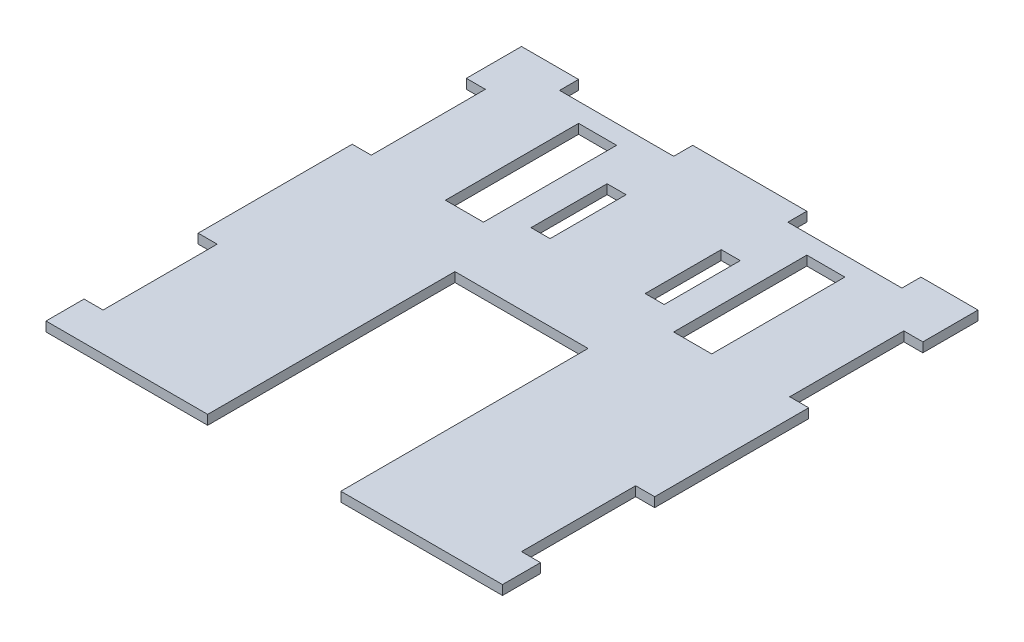
SolidWorks part; units mm, degrees
ref_plane "Front Plane" through (0, 0, 0) normal (0, 0, 1) x (1, 0, 0)
ref_plane "Top Plane" through (0, 0, 0) normal (0, 1, 0) x (1, 0, 0)
ref_plane "Right Plane" through (0, 0, 0) normal (1, 0, 0) x (0, 0, -1)
sketch "Sketch1" plane through (0, 0, 0) normal (0, 1, 0) x (1, 0, 0)
  line L0 (0, -3.4925) -> (0, 3.4925) construction
  line L1 (-152.4, -76.2) -> (152.4, -76.2)
  line L2 (-152.4, -76.2) -> (-152.4, 76.2)
  line L3 (-152.4, 76.2) -> (152.4, 76.2)
  line L4 (152.4, -76.2) -> (152.4, 76.2)
  line L5 (-152.4, -76.2) -> (152.4, 76.2) construction
  line L6 (-152.4, 76.2) -> (152.4, -76.2) construction
  line L7 (-152.4, -76.2) -> (-31.75, -76.2)
  line L8 (-152.4, -76.2) -> (-152.4, -241.3)
  line L9 (-152.4, -241.3) -> (-31.75, -241.3)
  line L10 (-31.75, -76.2) -> (-31.75, -241.3)
  line L11 (31.75, -76.2) -> (31.75, -241.3)
  line L12 (152.4, -241.3) -> (31.75, -241.3)
  line L13 (152.4, -76.2) -> (152.4, -241.3)
  line L14 (152.4, -76.2) -> (31.75, -76.2)
  line L15 (-44.45, -76.2) -> (-44.45, -241.3)
  line L16 (44.45, -76.2) -> (44.45, -241.3)
  point P0 (0, 0)
  dimension "D1" = 304.8
  dimension "D2" = 152.4
  dimension "D3" = 317.5
  dimension "D4" = 120.65
  dimension "D5" = 12.7
extrude "Boss-Extrude1" add sketch "Sketch1" along normal blind 6.35 contours L15 L1 L8 L9 | L14 L16 L12 L13 | L1 L7 L14 L4 L3 L2
sketch "Sketch2" plane through (0, 6.35, 0) normal (0, 1, 0) x (1, 0, 0)
  line L0 (152.4, -241.3) -> (152.4, 76.2) construction
  line L1 (152.4, 39.37) -> (139.7, 39.37)
  line L2 (152.4, 39.37) -> (152.4, -36.83)
  line L3 (152.4, -36.83) -> (139.7, -36.83)
  line L4 (139.7, 39.37) -> (139.7, -36.83)
  line L5 (-152.4, 76.2) -> (152.4, 76.2) construction
  line L6 (152.4, -139.7) -> (139.7, -139.7)
  line L7 (152.4, -139.7) -> (152.4, -215.9)
  line L8 (152.4, -215.9) -> (139.7, -215.9)
  line L9 (139.7, -139.7) -> (139.7, -215.9)
  line L10 (0, -3.4925) -> (0, 3.4925) construction
  line L11 (-152.4, -215.9) -> (-139.7, -215.9)
  line L12 (-139.7, -139.7) -> (-139.7, -215.9)
  line L13 (-152.4, -139.7) -> (-139.7, -139.7)
  line L14 (-152.4, -139.7) -> (-152.4, -215.9)
  line L15 (-152.4, -36.83) -> (-139.7, -36.83)
  line L16 (-139.7, 39.37) -> (-139.7, -36.83)
  line L17 (-152.4, 39.37) -> (-139.7, 39.37)
  line L18 (-152.4, 39.37) -> (-152.4, -36.83)
  line L19 (-114.3, 63.5) -> (-38.1, 63.5)
  line L20 (114.3, 76.2) -> (38.1, 76.2)
  line L21 (114.3, 76.2) -> (114.3, 63.5)
  line L22 (114.3, 63.5) -> (38.1, 63.5)
  line L23 (38.1, 76.2) -> (38.1, 63.5)
  line L24 (-38.1, 76.2) -> (-38.1, 63.5)
  line L25 (-114.3, 76.2) -> (-38.1, 76.2)
  line L26 (-114.3, 76.2) -> (-114.3, 63.5)
  line L27 (-88.9, -38.1) -> (-63.5, -38.1)
  line L28 (88.9, 50.8) -> (63.5, 50.8)
  line L29 (88.9, 50.8) -> (88.9, -38.1)
  line L30 (88.9, -38.1) -> (63.5, -38.1)
  line L31 (63.5, 50.8) -> (63.5, -38.1)
  line L32 (-63.5, 50.8) -> (-63.5, -38.1)
  line L33 (-88.9, 50.8) -> (-63.5, 50.8)
  line L34 (-88.9, 50.8) -> (-88.9, -38.1)
  dimension "D1" = 12.7
  dimension "D2" = 12.7
  dimension "D3" = 76.2
  dimension "D4" = 76.2
  dimension "D5" = 36.83
  dimension "D6" = 215.9
  dimension "D7" = 76.2
  dimension "D8" = 12.7
  dimension "D9" = 76.2
  dimension "D10" = 25.4
  dimension "D11" = 114.3
  dimension "D12" = 63.5
  dimension "D13" = 88.9
extrude "Cut-Extrude1" cut sketch "Sketch2" against normal through all
sketch "Sketch3" plane through (0, 6.35, 0) normal (0, 1, 0) x (1, 0, 0)
  line L0 (-44.45, -76.2) -> (44.45, -76.2) construction
  line L1 (-44.45, -25.4) -> (-31.75, -25.4)
  line L2 (-44.45, -25.4) -> (-44.45, 25.4)
  line L3 (-44.45, 25.4) -> (-31.75, 25.4)
  line L4 (-31.75, -25.4) -> (-31.75, 25.4)
  line L5 (0, -3.4925) -> (0, 3.4925) construction
  line L6 (44.45, 25.4) -> (31.75, 25.4)
  line L7 (31.75, -25.4) -> (31.75, 25.4)
  line L8 (44.45, -25.4) -> (31.75, -25.4)
  line L9 (44.45, -25.4) -> (44.45, 25.4)
  dimension "D1" = 50.8
  dimension "D2" = 12.7
  dimension "D3" = 50.8
extrude "Cut-Extrude2" cut sketch "Sketch3" against normal through all
